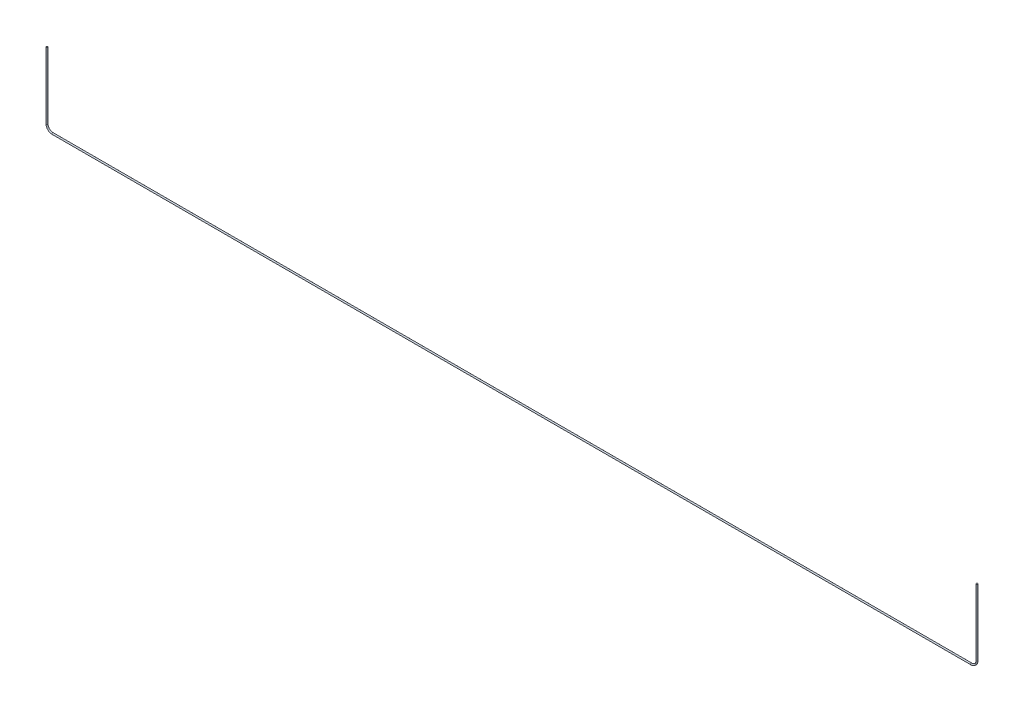
SolidWorks part; units mm, degrees
ref_plane "Front Plane" through (0, 0, 0) normal (0, 0, 1) x (1, 0, 0)
ref_plane "Top Plane" through (0, 0, 0) normal (0, 1, 0) x (1, 0, 0)
ref_plane "Right Plane" through (0, 0, 0) normal (1, 0, 0) x (0, 0, -1)
sketch "Sketch6" plane through (0, 0, 0) normal (0, 0, 1) x (1, 0, 0)
  line L0 (4070, 0) -> (-4070, 0)
  line L1 (-4120, 50) -> (-4120, 640)
  line L2 (0, 430.852) -> (0, -498.1376) construction
  line L3 (4120, 50) -> (4120, 640)
  arc A0 (-4070, 0) -> (-4120, 50) centre (-4070, 50) cw
  arc A1 (4070, 0) -> (4120, 50) centre (4070, 50) ccw
  point P6 (-4120, 0)
  point P10 (0, 0)
  dimension "D3" = 50
  dimension "D1" = 4120
  dimension "D2" = 640
sweep "Sweep2" add path "Sketch6" circular profile diameter 12.7 parameters "D3"=12.7
